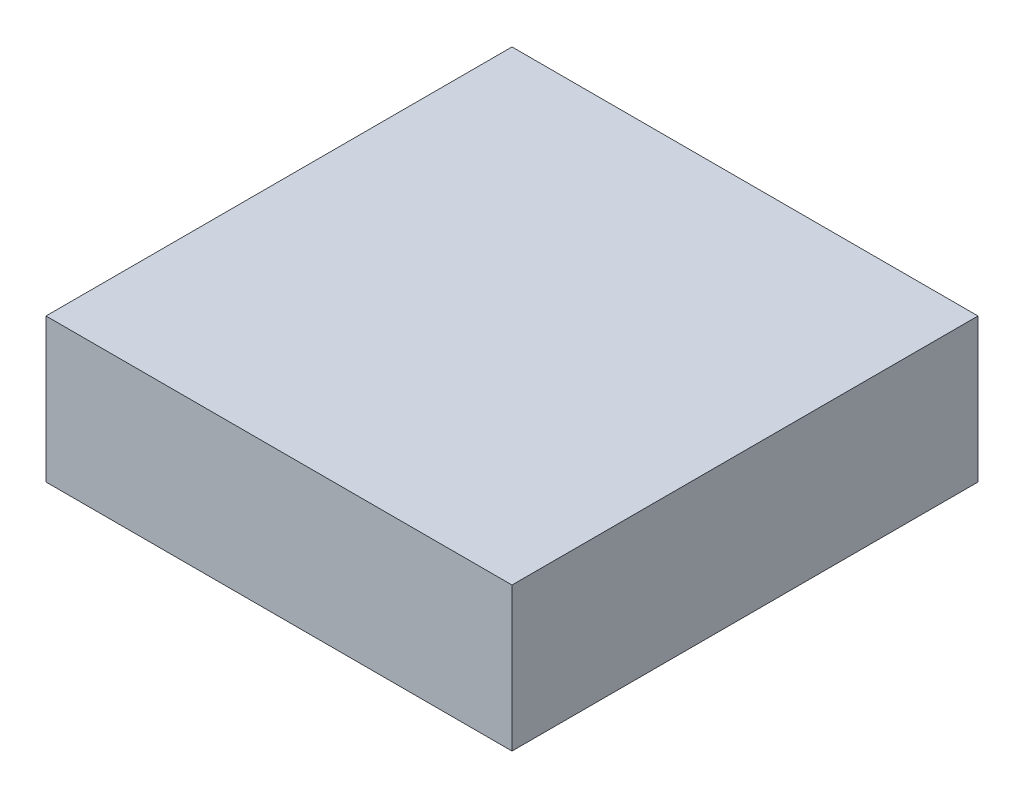
SolidWorks part; units mm, degrees
ref_plane "Front Plane" through (0, 0, 0) normal (0, 0, 1) x (1, 0, 0)
ref_plane "Top Plane" through (0, 0, 0) normal (0, 1, 0) x (1, 0, 0)
ref_plane "Right Plane" through (0, 0, 0) normal (1, 0, 0) x (0, 0, -1)
sketch "Sketch1" plane through (0, 0, 0) normal (0, 1, 0) x (1, 0, 0)
  line L1 (32.4, -32.4) -> (-32.4, -32.4)
  line L2 (32.4, -32.4) -> (32.4, 32.4)
  line L3 (32.4, 32.4) -> (-32.4, 32.4)
  line L4 (-32.4, -32.4) -> (-32.4, 32.4)
  line L5 (32.4, -32.4) -> (-32.4, 32.4) construction
  line L6 (32.4, 32.4) -> (-32.4, -32.4) construction
  point P0 (0, 0)
  dimension "D2" = 64.8
extrude "Boss-Extrude1" add sketch "Sketch1" along normal blind 20
